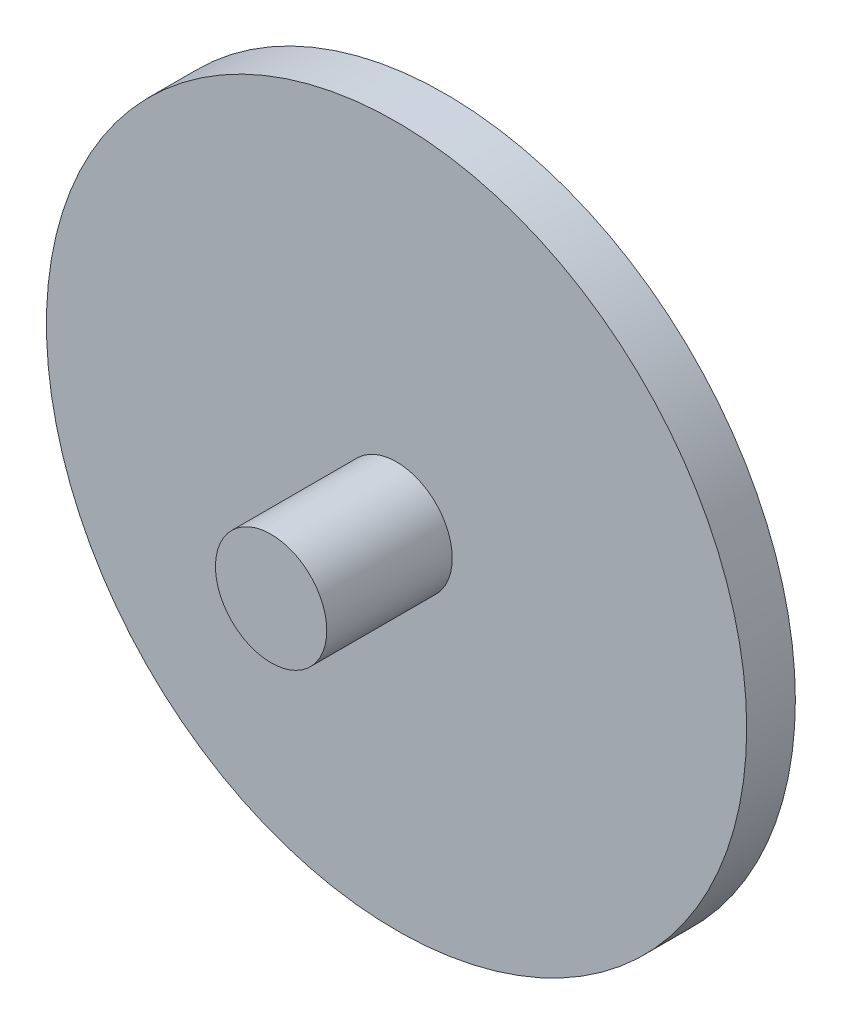
SolidWorks part; units mm, degrees
ref_plane "前视基准面" through (0, 0, 0) normal (0, 0, 1) x (1, 0, 0)
ref_plane "上视基准面" through (0, 0, 0) normal (0, 1, 0) x (1, 0, 0)
ref_plane "右视基准面" through (0, 0, 0) normal (1, 0, 0) x (0, 0, -1)
sketch "草图1" plane through (0, 0, 0) normal (0, 0, 1) x (1, 0, 0)
  circle A0 centre (0, 0) radius 95
  dimension "D1" = 190
extrude "凸台-拉伸1" add sketch "草图1" along normal blind 13.208
sketch "草图2" plane through (0, 0, 13.208) normal (0, 0, 1) x (1, 0, 0)
  circle A0 centre (0, 0) radius 6.2806
  circle A1 centre (0, 0) radius 8.8206
  dimension "D1" = 2.54
extrude "切除-拉伸1" cut sketch "草图2" against normal blind 3.302
sketch "草图3" plane through (0, 0, 13.208) normal (0, 0, 1) x (1, 0, 0)
  circle A0 centre (0, 0) radius 15.1014
extrude "凸台-拉伸2" add sketch "草图3" along normal blind 34.036
